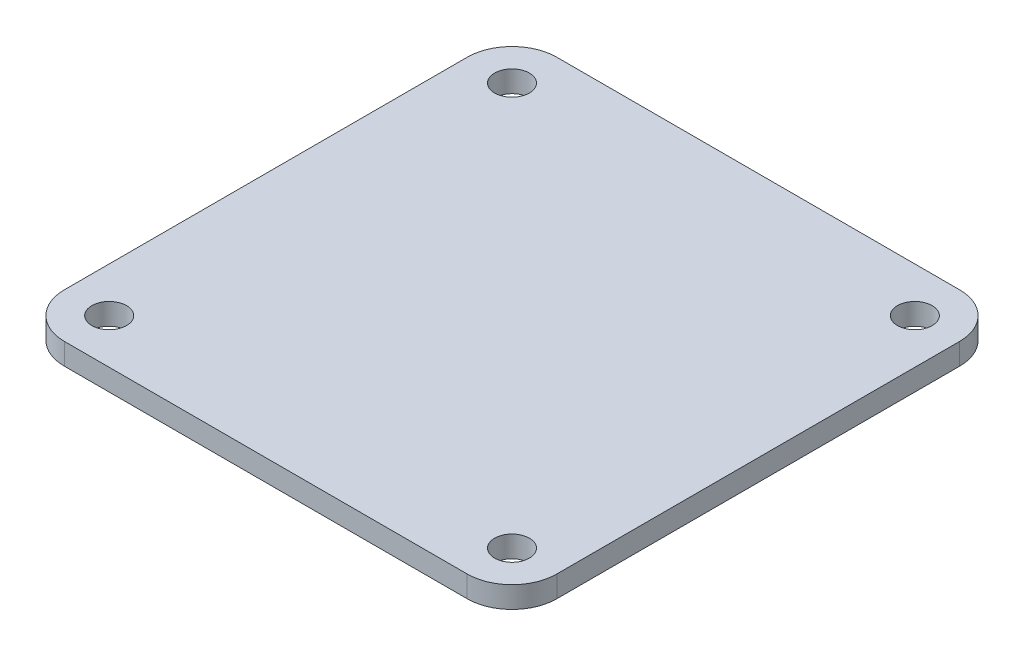
SolidWorks part; units mm, degrees
ref_plane "Front Plane" through (0, 0, 0) normal (0, 0, 1) x (1, 0, 0)
ref_plane "Top Plane" through (0, 0, 0) normal (0, 1, 0) x (1, 0, 0)
ref_plane "Right Plane" through (0, 0, 0) normal (1, 0, 0) x (0, 0, -1)
sketch "Sketch1" plane through (0, 0, 0) normal (0, 1, 0) x (1, 0, 0)
  line L1 (0, 0) -> (69.85, 0)
  line L2 (0, 0) -> (0, 69.85)
  line L3 (0, 69.85) -> (69.85, 69.85)
  line L4 (69.85, 0) -> (69.85, 69.85)
  dimension "D1" = 69.85
  dimension "D2" = 69.85
sketch "Sketch2" plane through (0, 0, 0) normal (0, 1, 0) x (1, 0, 0)
  line L0 (0, 0) -> (69.85, 0) construction
  line L1 (0, 0) -> (0, 69.85) construction
  line L2 (69.85, 0) -> (69.85, 69.85) construction
  line L3 (0, 69.85) -> (69.85, 69.85) construction
  circle A0 centre (6.35, 6.35) radius 2.46
  circle A1 centre (63.5, 6.35) radius 2.46
  circle A2 centre (6.35, 63.5) radius 2.46
  circle A3 centre (63.5, 63.5) radius 2.46
  point P2 (4.4346, 4.3956)
  point P9 (63.4061, 6.35)
  point P12 (6.35, 63.5103)
  point P15 (63.4061, 64.9416)
  dimension "D1" = 6.35
  dimension "D2" = 6.35
  dimension "D3" = 6.35
  dimension "D4" = 6.35
  dimension "D5" = 6.35
  dimension "D6" = 6.35
  dimension "D7" = 6.35
  dimension "D8" = 6.35
extrude "Boss-Extrude1" add sketch "Sketch1" along normal blind 3.048
extrude "Cut-Extrude1" cut sketch "Sketch2" along normal through all
fillet "Fillet2" radius 6.35 4 edges at (0, 1.524, -69.85) (0, 1.524, 0) (69.85, 1.524, -69.85) (69.85, 1.524, 0)
